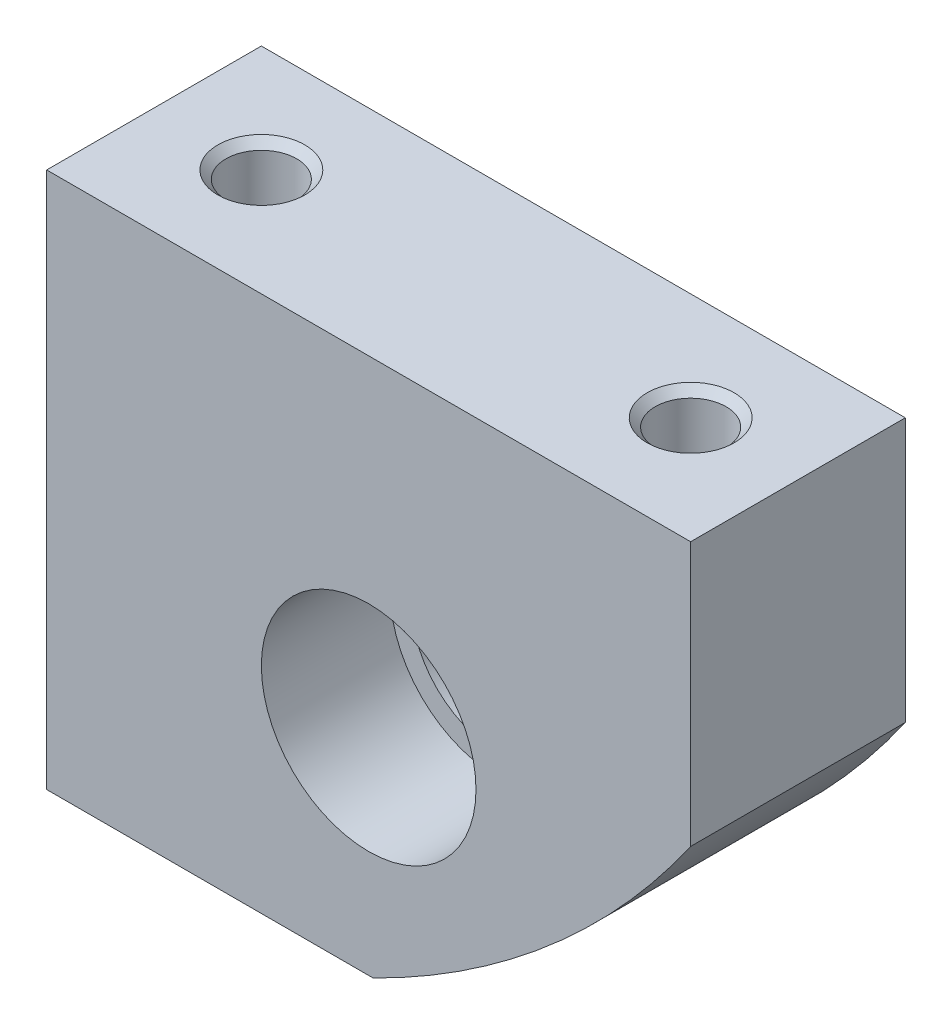
SolidWorks part; units mm, degrees
ref_plane "Ebene vorne" through (0, 0, 0) normal (0, 0, 1) x (1, 0, 0)
ref_plane "Ebene oben" through (0, 0, 0) normal (0, 1, 0) x (1, 0, 0)
ref_plane "Ebene rechts" through (0, 0, 0) normal (1, 0, 0) x (0, 0, -1)
sketch "Skizze1" plane through (0, 0, 0) normal (0, 0, 1) x (1, 0, 0)
  line L1 (-18.8857, 20.1408) -> (11.1143, 20.1408)
  line L2 (-18.8857, 20.1408) -> (-18.8857, -4.8592)
  line L3 (-18.8857, -4.8592) -> (11.1143, -4.8592)
  line L4 (11.1143, 20.1408) -> (11.1143, -4.8592)
  circle A0 centre (-3.8857, 5.1408) radius 4
  dimension "D3" = 15
  dimension "D1" = 25
  dimension "D2" = 30
extrude "Aufsatz-Linear austragen1" add sketch "Skizze1" along normal blind 10
sketch "Skizze2" plane through (0, 0, 10) normal (0, 0, 1) x (1, 0, 0)
  circle A1 centre (-3.8857, 5.1408) radius 5
extrude "Schnitt-Linear austragen1" cut sketch "Skizze2" against normal blind 6
sketch "Skizze3" plane through (0, 20.1408, 0) normal (0, 1, 0) x (1, 0, 0)
  line L0 (-18.8857, -10) -> (-18.8857, 0) construction
  line L1 (11.1143, -10) -> (11.1143, 0) construction
  circle A0 centre (-13.8857, -5) radius 1
  circle A1 centre (6.1143, -5) radius 1
  dimension "D1" = 5
  dimension "D2" = 5
extrude "Schnitt-Linear austragen2" cut sketch "Skizze3" against normal blind 16
hole_wizard "M4 Gewindebohrung1" positions "3D-Skizze1" profile "Skizze4" tap size "M4" standard "DIN"
sketch3d "3D-Skizze1"
  line L0 (-13.8857, 4.1408, 5) -> (-13.8857, 20.1408, 5) construction
  line L1 (6.1143, 4.1408, 5) -> (6.1143, 20.1408, 5) construction
  point P0 (-13.8857, 20.1408, 5)
  point P4 (6.1143, 20.1408, 5)
sketch "Skizze4" plane through (-13.8857, 20.1408, 5) normal (1, 0, 0) x (0, 0, 1)
  line L0 (0, 0) -> (0, 12.4914)
  line L1 (0, 12.4914) -> (1.65, 11.5)
  line L2 (1.65, 11.5) -> (1.65, 0.375)
  line L3 (1.65, 0.375) -> (2.025, 0)
  line L5 (2.025, 0) -> (0, 0)
  line L6 (-1.65, 0.375) -> (-2.025, 0) construction
  line L10 (0, 12.4914) -> (-1.65, 11.5) construction
  line L11 (0, -6.35) -> (0, 107.95) construction
  dimension "Bohrerdurchmesser" = 3.3
  dimension "Bohrungstiefe" = 11.5
  dimension "Senkdurchmesser (Oben)" = 4.05
  dimension "Senkwinkel (Oben)" = 90
  dimension "Spitzenwinkel" = 118
cosmetic thread "Bohrungsgewinde1"
cosmetic thread "Bohrungsgewinde2"
sketch "Skizze5" plane through (0, 0, 10) normal (0, 0, 1) x (1, 0, 0)
  line L2 (-18.8857, 20.1408) -> (-18.8857, -4.8592) construction
  line L3 (-18.8857, -4.8592) -> (11.1143, -4.8592) construction
  circle A1 centre (-20.8857, 30.1408) radius 39
  circle A2 centre (-20.8857, 30.1408) radius 51.2073
  dimension "D1" = 2
  dimension "D2" = 35
extrude "Schnitt-Linear austragen3" cut sketch "Skizze5" against normal blind 10
